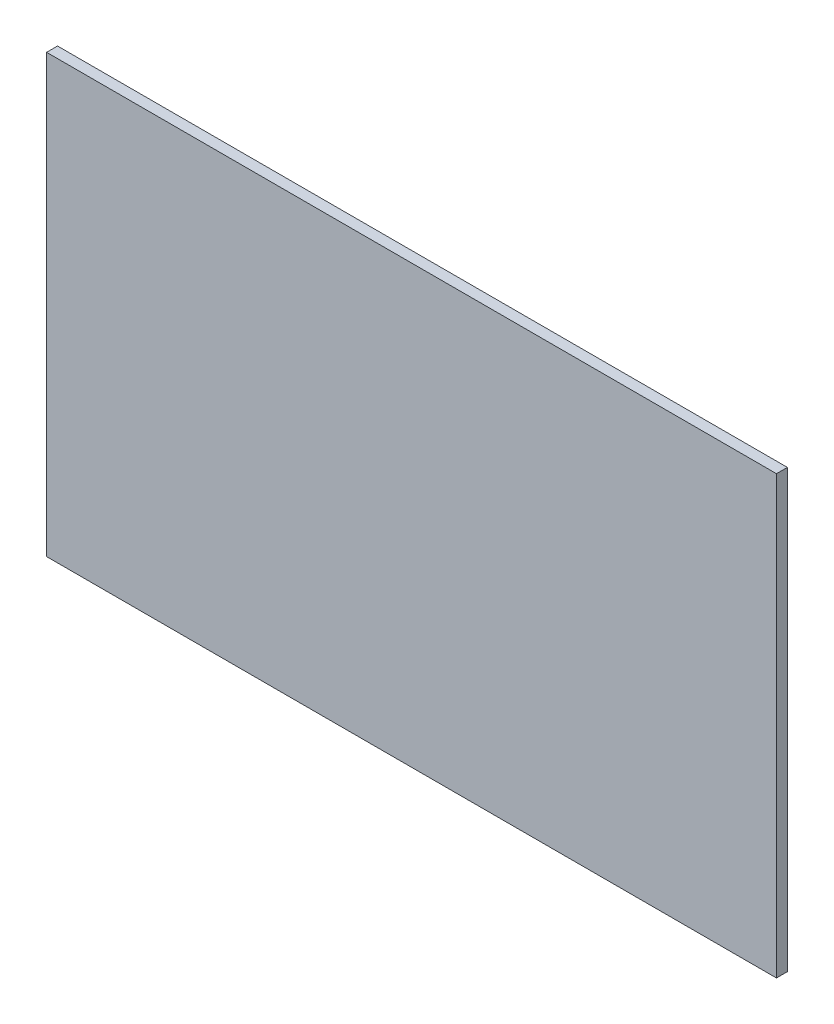
SolidWorks part; units mm, degrees
ref_plane "Спереди" through (0, 0, 0) normal (0, 0, 1) x (1, 0, 0)
ref_plane "Сверху" through (0, 0, 0) normal (0, 1, 0) x (1, 0, 0)
ref_plane "Справа" through (0, 0, 0) normal (1, 0, 0) x (0, 0, -1)
sketch "Эскиз1" plane through (0, 0, 0) normal (0, 1, 0) x (1, 0, 0)
  line L1 (-90.2767, 0) -> (76.8413, 0)
  line L2 (-90.2767, 0) -> (-90.2767, -2.5)
  line L3 (-90.2767, -2.5) -> (76.8413, -2.5)
  line L4 (76.8413, 0) -> (76.8413, -2.5)
extrude "Вытянуть1" add sketch "Эскиз1" along normal blind 100
